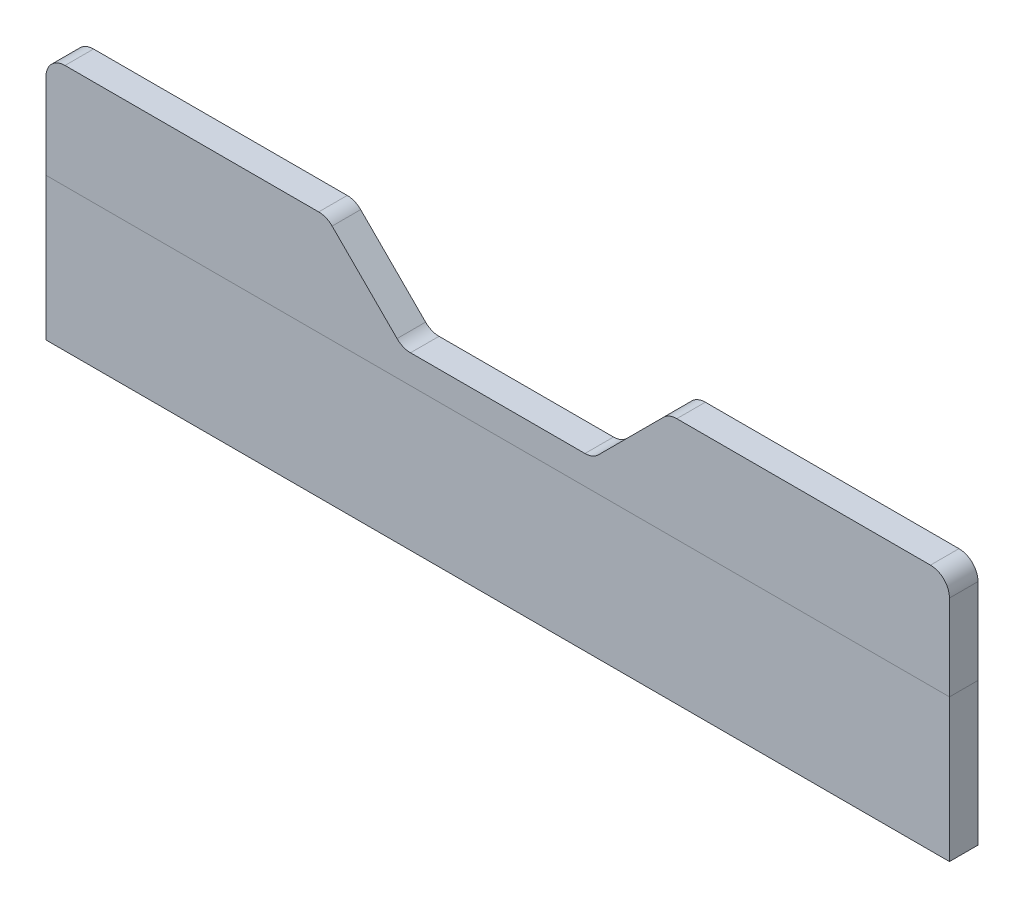
SolidWorks part; units mm, degrees
material "Pine"
ref_plane "Piano frontale" through (0, 0, 0) normal (0, 0, 1) x (1, 0, 0)
ref_plane "Piano superiore" through (0, 0, 0) normal (0, 1, 0) x (1, 0, 0)
ref_plane "Piano destro" through (0, 0, 0) normal (1, 0, 0) x (0, 0, -1)
sketch "Sketch1" plane through (0, 0, 0) normal (0, 0, 1) x (1, 0, 0)
  line L1 (0, 0) -> (47.5, 0)
  line L2 (0, 0) -> (0, 7.5)
  line L3 (0, 7.5) -> (47.5, 7.5)
  line L4 (47.5, 0) -> (47.5, 7.5)
  dimension "D1" = 47.5
  dimension "D2" = 7.5
extrude "Boss-Extrude1" add sketch "Sketch1" against normal blind 1.5
sketch "Sketch2" plane through (0, 0, 0) normal (0, 0, 1) x (1, 0, 0)
  line L0 (47.5, 0) -> (47.5, 7.5) construction
  line L1 (0, 7.5) -> (47.5, 7.5)
  line L2 (0, 7.5) -> (0, 13)
  line L3 (0, 13) -> (14.75, 13)
  line L4 (47.5, 7.5) -> (47.5, 13)
  line L5 (18.75, 9) -> (28.75, 9)
  line L10 (32.75, 13) -> (47.5, 13)
  line L11 (14.75, 13) -> (18.75, 9)
  line L12 (32.75, 13) -> (28.75, 9)
  point P9 (23.75, 9)
  point P10 (23.75, 7.5)
  dimension "D1" = 5.5
  dimension "D2" = 10
  dimension "D3" = 4
  dimension "D4" = 135
  dimension "D5" = 135
extrude "Boss-Extrude2" add sketch "Sketch2" against normal blind 1.5 separate body
fillet "Fillet1" radius 1 6 edges at (47.5, 13, -0.75) (0, 13, -0.75) (32.75, 13, -0.75) (28.75, 9, -0.75) (18.75, 9, -0.75) (14.75, 13, -0.75)
scale "Scale1" bodies to scale 101 102 scale about origin uniform scaling yes scale factor 10
